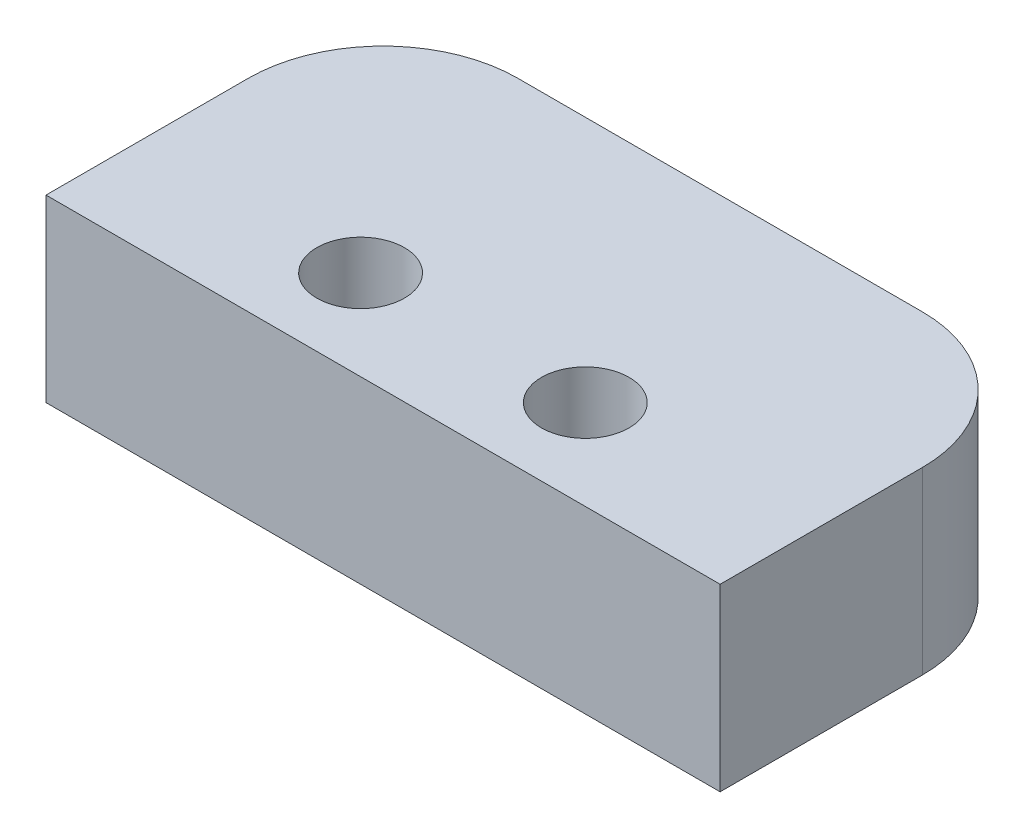
SolidWorks part; units mm, degrees
ref_plane "Спереди" through (0, 0, 0) normal (0, 0, 1) x (1, 0, 0)
ref_plane "Сверху" through (0, 0, 0) normal (0, 1, 0) x (1, 0, 0)
ref_plane "Справа" through (0, 0, 0) normal (1, 0, 0) x (0, 0, -1)
sketch "Эскиз1" plane through (0, 0, 0) normal (0, 1, 0) x (1, 0, 0)
  line L1 (15, -7.5) -> (-15, -7.5)
  line L2 (15, -7.5) -> (15, 7.5)
  line L3 (15, 7.5) -> (-15, 7.5)
  line L4 (-15, -7.5) -> (-15, 7.5)
  line L5 (15, -7.5) -> (-15, 7.5) construction
  line L6 (15, 7.5) -> (-15, -7.5) construction
  point P0 (0, 0)
  dimension "D1" = 30
  dimension "D2" = 15
extrude "Бобышка-Вытянуть1" add sketch "Эскиз1" along normal blind 8
fillet "Скругление1" radius 6 2 edges at (-15, 4, -7.5) (15, 4, -7.5)
sketch "Эскиз2" plane through (0, 8, 0) normal (0, 1, 0) x (1, 0, 0)
  line L0 (0, 9.5664) -> (0, -9.7823) construction
  line L1 (-15, -7.5) -> (15, -7.5) construction
  circle A0 centre (-5, -3.5) radius 1.95
  circle A1 centre (5, -3.5) radius 1.95
  dimension "D1" = 3.9
  dimension "D2" = 10
  dimension "D3" = 4
extrude "Вырез-Вытянуть1" cut sketch "Эскиз2" against normal through all
